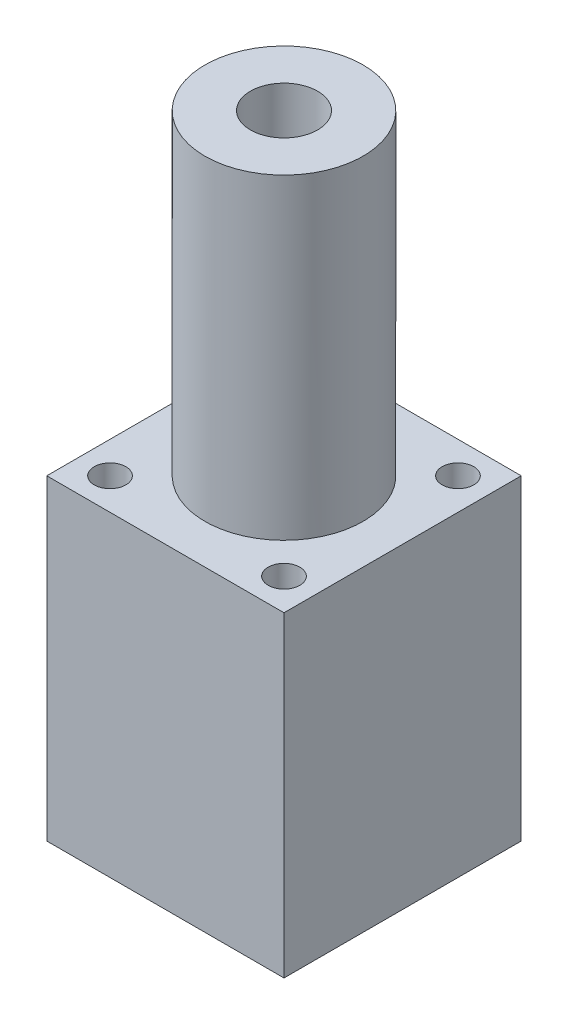
SolidWorks part; units mm, degrees
ref_plane "Ön Düzlem" through (0, 0, 0) normal (0, 0, 1) x (1, 0, 0)
ref_plane "Üst Düzlem" through (0, 0, 0) normal (0, 1, 0) x (1, 0, 0)
ref_plane "Sağ Düzlem" through (0, 0, 0) normal (1, 0, 0) x (0, 0, -1)
sketch "Çizim1" plane through (0, 0, 0) normal (0, 1, 0) x (1, 0, 0)
  line L1 (0, 0) -> (30, 0)
  line L2 (0, 0) -> (0, 30)
  line L3 (0, 30) -> (30, 30)
  line L4 (30, 0) -> (30, 30)
  dimension "D1" = 30
extrude "Yükseklik-Ekstrüzyon1" add sketch "Çizim1" along normal blind 40
sketch "Çizim2" plane through (0, 40, 0) normal (0, 1, 0) x (1, 0, 0)
  line L0 (30, 30) -> (0, 30) construction
  line L1 (0, 30) -> (0, 0) construction
  line L2 (30, 0) -> (30, 30) construction
  line L3 (0, 0) -> (30, 0) construction
  circle A0 centre (4, 26) radius 2
  circle A1 centre (26, 26) radius 2
  circle A2 centre (26, 4) radius 2
  circle A3 centre (4, 4) radius 2
  dimension "D1" = 4
  dimension "D2" = 4
  dimension "D4" = 4
  dimension "D5" = 4
  dimension "D3" = 4
extrude "Kes-Ekstrüzyon1" cut sketch "Çizim2" against normal blind 40
sketch "Çizim3" plane through (0, 40, 0) normal (0, 1, 0) x (1, 0, 0)
  line L0 (30, 0) -> (30, 30) construction
  line L1 (30, 30) -> (0, 30) construction
  circle A0 centre (15, 15) radius 10
  circle A1 centre (15, 15) radius 4.25
  dimension "D1" = 20
  dimension "D2" = 8.5
  dimension "D3" = 15
  dimension "D4" = 15
extrude "Yükseklik-Ekstrüzyon2" add sketch "Çizim3" along normal blind 40
